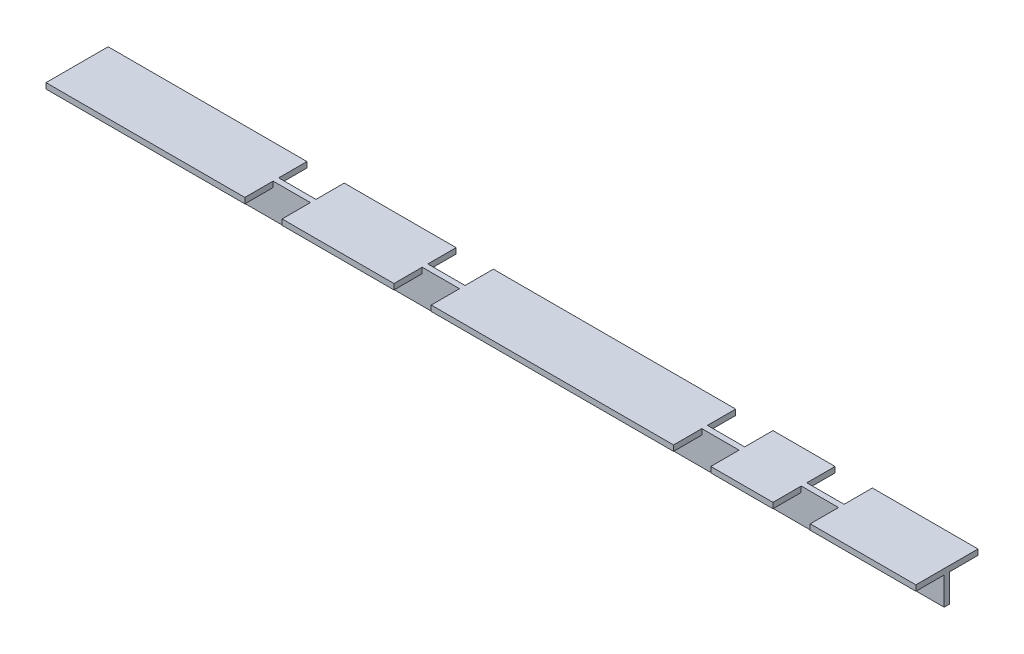
SolidWorks part; units mm, degrees
ref_plane "Front Plane" through (0, 0, 0) normal (0, 0, 1) x (1, 0, 0)
ref_plane "Top Plane" through (0, 0, 0) normal (0, 1, 0) x (1, 0, 0)
ref_plane "Right Plane" through (0, 0, 0) normal (1, 0, 0) x (0, 0, -1)
sketch "T" plane through (0, 0, 0) normal (1, 0, 0) x (0, 0, -1)
  line L0 (50, 0) -> (50, -54) construction
  line L1 (0, 0) -> (100, 0)
  line L2 (0, 0) -> (0, -9)
  line L3 (0, -9) -> (45.5, -9)
  line L4 (100, 0) -> (100, -9)
  line L6 (45.5, -9) -> (45.5, -54)
  line L7 (45.5, -54) -> (54.5, -54)
  line L8 (54.5, -9) -> (54.5, -54)
  line L9 (54.5, -9) -> (100, -9)
  dimension "D1" = 100
  dimension "D2" = 45
  dimension "D3" = 9
  dimension "D4" = 9
extrude "Boss-Extrude1" add sketch "T" along normal blind 1400
sketch "Sketch1" plane through (0, -9, 0) normal (0, -1, 0) x (-1, 0, 0)
  line L0 (-1400, 45.5) -> (0, 45.5) construction
  line L1 (-380, 45.5) -> (-320, 45.5)
  line L2 (-380, 45.5) -> (-380, 0)
  line L3 (-380, 0) -> (-320, 0)
  line L4 (-320, 45.5) -> (-320, 0)
  line L5 (-1400, 0) -> (0, 0) construction
  line L6 (-1400, 45.5) -> (0, 45.5) construction
  line L7 (-620, 45.5) -> (-560, 45.5)
  line L8 (-620, 45.5) -> (-620, 0)
  line L9 (-620, 0) -> (-560, 0)
  line L10 (-560, 45.5) -> (-560, 0)
  line L11 (-1230, 45.5) -> (-1170, 45.5)
  line L12 (-1230, 45.5) -> (-1230, 0)
  line L13 (-1230, 0) -> (-1170, 0)
  line L14 (-1170, 45.5) -> (-1170, 0)
  line L15 (-1400, 100) -> (0, 100) construction
  line L16 (-1230, 100) -> (-1170, 100)
  line L17 (-1230, 100) -> (-1230, 54.5)
  line L18 (-1230, 54.5) -> (-1170, 54.5)
  line L19 (-1170, 100) -> (-1170, 54.5)
  line L20 (-1400, 54.5) -> (0, 54.5) construction
  line L22 (-620, 100) -> (-560, 100)
  line L23 (-620, 100) -> (-620, 54.5)
  line L24 (-620, 54.5) -> (-560, 54.5)
  line L25 (-560, 100) -> (-560, 54.5)
  line L26 (-380, 100) -> (-320, 100)
  line L27 (-380, 100) -> (-380, 54.5)
  line L28 (-380, 54.5) -> (-320, 54.5)
  line L29 (-320, 100) -> (-320, 54.5)
  line L30 (-1400, 0) -> (0, 0) construction
  line L31 (-1070, 0) -> (-1010, 0)
  line L32 (-1070, 0) -> (-1070, 45.5)
  line L33 (-1070, 45.5) -> (-1010, 45.5)
  line L34 (-1010, 0) -> (-1010, 45.5)
  line L35 (-1400, 100) -> (0, 100) construction
  line L36 (-1070, 54.5) -> (-1010, 54.5)
  line L37 (-1070, 54.5) -> (-1070, 100)
  line L38 (-1070, 100) -> (-1010, 100)
  line L39 (-1010, 54.5) -> (-1010, 100)
  line L40 (-1400, 100) -> (-1400, 0) construction
  point P36 (-620, 77.25)
  point P37 (-1170, 77.25)
  dimension "D1" = 60
  dimension "D3" = 180
  dimension "D4" = 60
  dimension "D5" = 60
  dimension "D6" = 550
  dimension "D7" = 60
  dimension "D8" = 100
  dimension "D2" = 170
extrude "Cut-Extrude1" cut sketch "Sketch1" against normal through all contours L19 L18 L17 L16
equation "\"D4@Sketch1\"=\"D1@Sketch1\""
equation "\"D5@Sketch1\"=\"D1@Sketch1\""
equation "\"D7@Sketch1\"=\"D1@Sketch1\""
